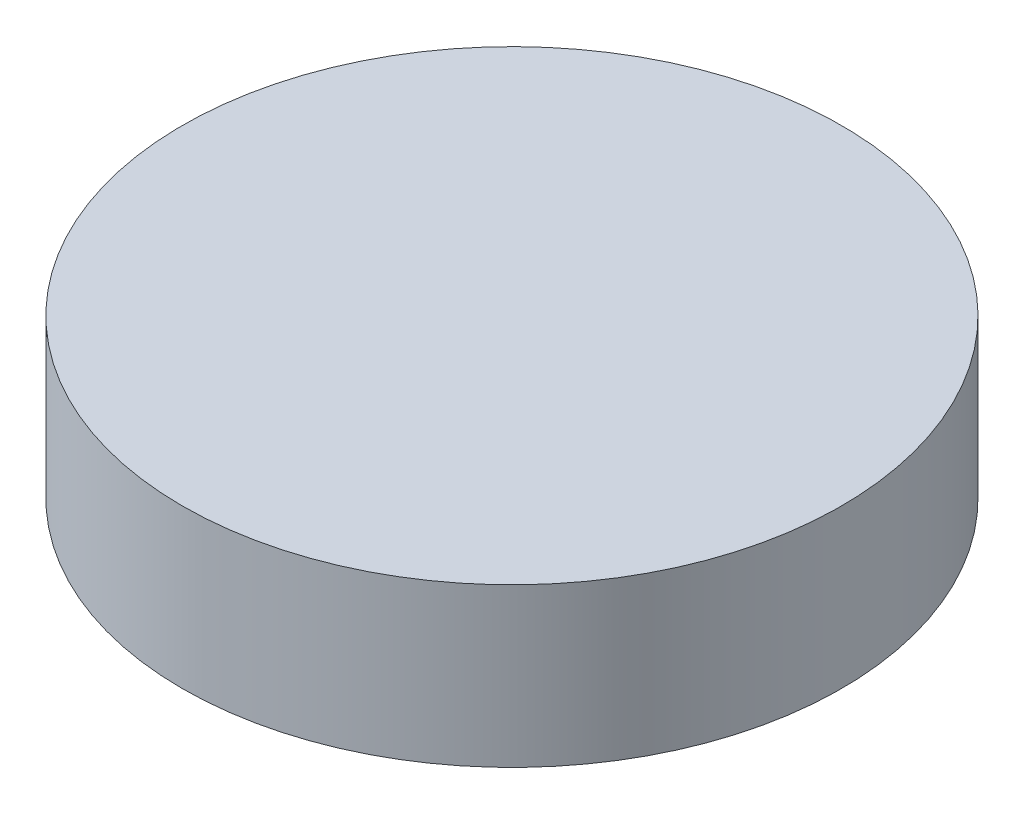
SolidWorks part; units mm, degrees
ref_plane "Front Plane" through (0, 0, 0) normal (0, 0, 1) x (1, 0, 0)
ref_plane "Top Plane" through (0, 0, 0) normal (0, 1, 0) x (1, 0, 0)
ref_plane "Right Plane" through (0, 0, 0) normal (1, 0, 0) x (0, 0, -1)
other "Configuration Table"
sketch "Sketch1" plane through (0, 0, 0) normal (0, 1, 0) x (1, 0, 0)
  circle A0 centre (650, 50) radius 25
extrude "TOPPING_ayar_ayagi_2" add sketch "Sketch1" along normal blind 12 separate body
